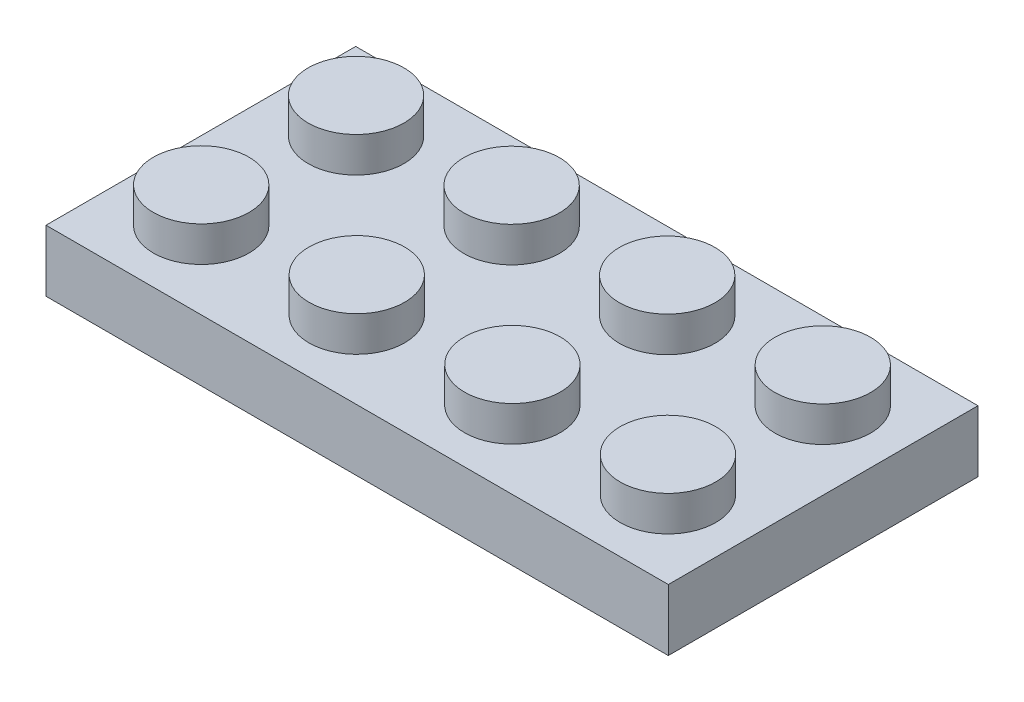
SolidWorks part; units mm, degrees
ref_plane "Front Plane" through (0, 0, 0) normal (0, 0, 1) x (1, 0, 0)
ref_plane "Top Plane" through (0, 0, 0) normal (0, 1, 0) x (1, 0, 0)
ref_plane "Right Plane" through (0, 0, 0) normal (1, 0, 0) x (0, 0, -1)
sketch "Sketch1" plane through (0, 0, 0) normal (0, 1, 0) x (1, 0, 0)
  line L1 (-15.925, 7.925) -> (15.925, 7.925)
  line L2 (-15.925, 7.925) -> (-15.925, -7.925)
  line L3 (-15.925, -7.925) -> (15.925, -7.925)
  line L4 (15.925, 7.925) -> (15.925, -7.925)
  line L5 (-15.925, 7.925) -> (15.925, -7.925) construction
  line L6 (-15.925, -7.925) -> (15.925, 7.925) construction
  point P0 (0, 0)
  dimension "D1" = 31.85
  dimension "D2" = 15.85
extrude "Boss-Extrude1" add sketch "Sketch1" against normal blind 3.15
sketch "Sketch2" plane through (0, 0, 0) normal (0, 1, 0) x (1, 0, 0)
  line L0 (15.925, -7.925) -> (15.925, 7.925) construction
  line L1 (-15.925, 7.925) -> (-15.925, -7.925) construction
  line L2 (15.925, 7.925) -> (-15.925, 7.925) construction
  circle A0 centre (-11.9438, 3.9625) radius 2.45
  circle A1 centre (-3.9813, 3.9625) radius 2.45
  circle A2 centre (3.9812, 3.9625) radius 2.45
  circle A3 centre (11.9437, 3.9625) radius 2.45
  circle A4 centre (-3.9813, -3.9625) radius 2.45
  circle A5 centre (3.9812, -3.9625) radius 2.45
  circle A6 centre (11.9437, -3.9625) radius 2.45
  circle A7 centre (-11.9438, -3.9625) radius 2.45
  dimension "D1" = 4.9
  dimension "D2" = 3.9813
  dimension "D6" = 7.925
  dimension "D7" = 7.9625
  dimension "D8" = 3.9813
  dimension "D3" = 3.9625
  dimension "D4" = 4
  dimension "D5" = 2
extrude "Boss-Extrude2" add sketch "Sketch2" along normal blind 1.8
shell "Shell1" thickness 1.5
sketch "Sketch3" plane through (0, -1.5, 0) normal (0, -1, 0) x (1, 0, 0)
  line L0 (0, 10.4627) -> (0, -10.6693) construction
  line L2 (15.925, -7.925) -> (-15.925, -7.925) construction
  circle A0 centre (0, 0) radius 2.37
  circle A1 centre (0, 0) radius 3.23
  circle A2 centre (7.9625, 0) radius 3.23
  circle A3 centre (7.9625, 0) radius 2.37
  circle A4 centre (-7.9625, 0) radius 2.37
  circle A5 centre (-7.9625, 0) radius 3.23
  dimension "D1" = 3.23
  dimension "D2" = 2.37
  dimension "D3" = 6.46
  dimension "D4" = 4.74
  dimension "D5" = 7.9625
  dimension "D6" = 7.925
extrude "Boss-Extrude3" add sketch "Sketch3" along normal offset from surface (1.45 mm away) 0.2 up to face at (0, -3.15, 0)
